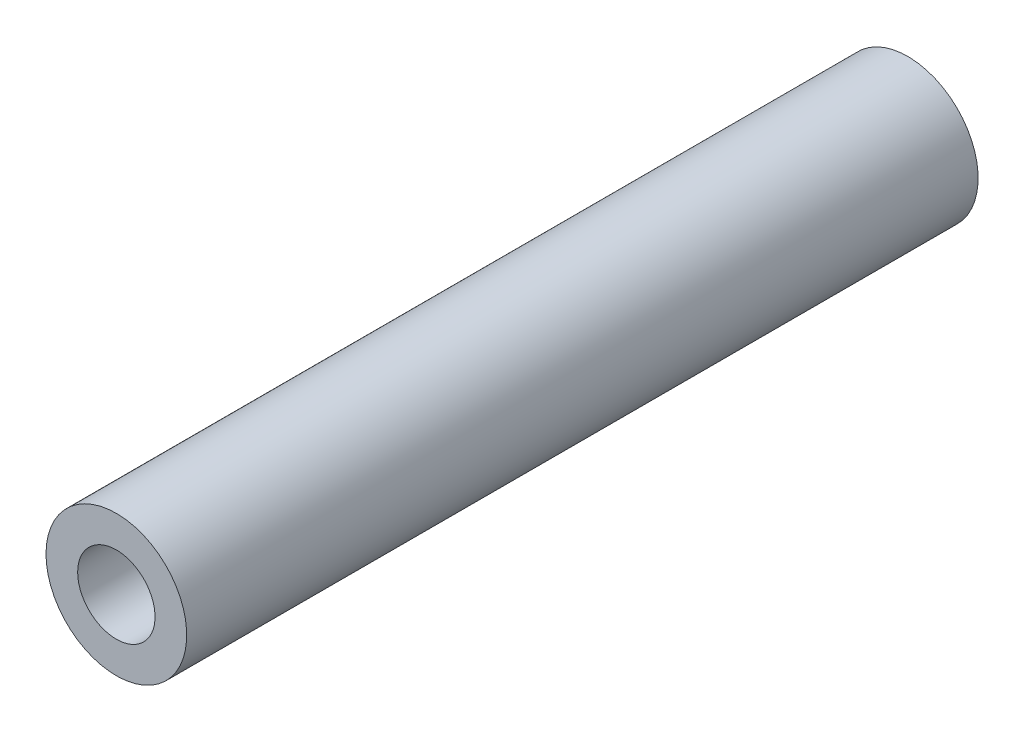
SolidWorks part; units mm, degrees
ref_plane "Front Plane" through (0, 0, 0) normal (0, 0, 1) x (1, 0, 0)
ref_plane "Top Plane" through (0, 0, 0) normal (0, 1, 0) x (1, 0, 0)
ref_plane "Right Plane" through (0, 0, 0) normal (1, 0, 0) x (0, 0, -1)
sketch "M4 sleeve profile" plane through (0, 0, 0) normal (0, 0, 1) x (1, 0, 0)
  circle A0 centre (0, 0) radius 4
  circle A1 centre (0, 0) radius 2.2
extrude "M4 sleeve" add sketch "M4 sleeve profile" along normal blind 45
